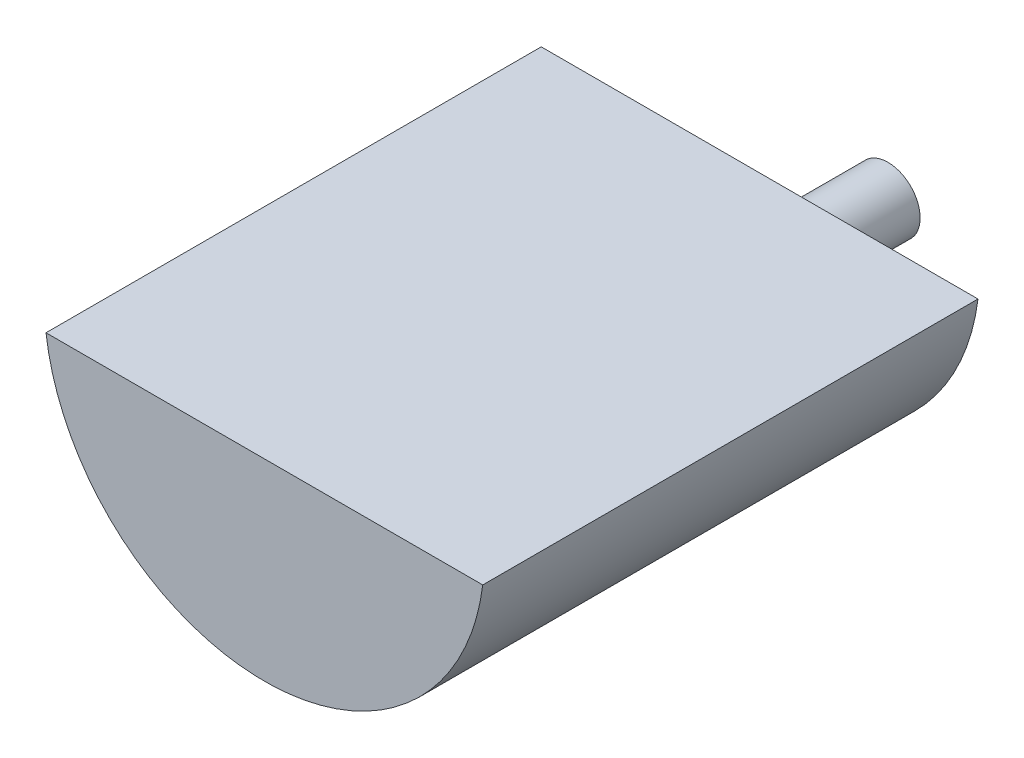
SolidWorks part; units mm, degrees
material "Silicon Dioxide"
ref_plane "Front Plane" through (0, 0, 0) normal (0, 0, 1) x (1, 0, 0)
ref_plane "Top Plane" through (0, 0, 0) normal (0, 1, 0) x (1, 0, 0)
ref_plane "Right Plane" through (0, 0, 0) normal (1, 0, 0) x (0, 0, -1)
sketch "Sketch1" plane through (0, 0, 0) normal (0, 0, 1) x (1, 0, 0)
  circle A0 centre (0, 0) radius 24
  dimension "D1" = 48
extrude "Boss-Extrude1" add sketch "Sketch1" along normal blind 54
sketch "Sketch2" plane through (0, 0, 0) normal (0, 0, -1) x (-1, 0, 0)
  line L1 (-47.0082, 33.2532) -> (42.992, 33.2532)
  line L2 (-47.0082, 33.2532) -> (-47.0082, -3)
  line L3 (-47.0082, -3) -> (42.992, -3)
  line L4 (42.992, 33.2532) -> (42.992, -3)
  dimension "D1" = 3
extrude "Cut-Extrude1" cut sketch "Sketch2" against normal through all
sketch "Sketch3" plane through (0, 0, 0) normal (0, 0, -1) x (-1, 0, 0)
  circle A0 centre (0, -12.5) radius 1
  circle A1 centre (0, -12.5) radius 3.5
  dimension "D2" = 2
  dimension "D3" = 7
  dimension "D1" = 12.5
extrude "Boss-Extrude2" add sketch "Sketch3" along normal blind 14
ref_plane "Plane1" through (0, 0, 51) normal (0, 0, 1) x (1, 0, 0)
sketch "Sketch4" plane through (0, 0, 51) normal (0, 0, 1) x (1, 0, 0)
  line L2 (20.1246, -6) -> (-20.1246, -6)
  line L3 (20.1246, -6) -> (-20.1246, -6)
  arc A1 (-20.1246, -6) -> (20.1246, -6) centre (0, 0) ccw
  arc A4 (-20.1246, -6) -> (20.1246, -6) centre (0, 0) ccw
  dimension "D1" = 3
extrude "Cut-Extrude2" cut sketch "Sketch4" against normal blind 48
sketch "Sketch5" plane through (0, 0, 0) normal (0, 0, -1) x (-1, 0, 0)
  circle A0 centre (0, -12.5) radius 1 construction
  circle A1 centre (0, -12.5) radius 1
extrude "Cut-Extrude3" cut sketch "Sketch5" against normal blind 3
fillet "Fillet1" [suppressed] radius 0.5
ref_plane "Plane2" through (0, -6, 0) normal (0, 1, 0) x (1, 0, 0)
sketch "Sketch6" plane through (0, -6, 0) normal (0, 1, 0) x (1, 0, 0)
  line L1 (27.5911, -67.0457) -> (-23.8724, -67.0457)
  line L2 (27.5911, -67.0457) -> (27.5911, 15.703)
  line L3 (27.5911, 15.703) -> (-23.8724, 15.703)
  line L4 (-23.8724, -67.0457) -> (-23.8724, 15.703)
extrude "Cut-Extrude4" [suppressed] cut sketch "Sketch6" along normal blind 10
